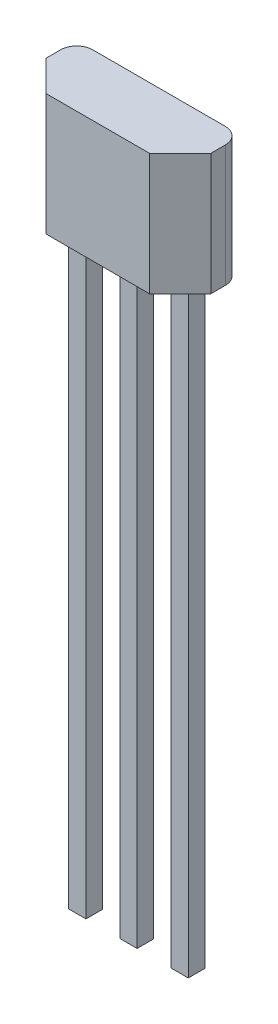
SolidWorks part; units mm, degrees
ref_plane "Front Plane" through (0, 0, 0) normal (0, 0, 1) x (1, 0, 0)
ref_plane "Top Plane" through (0, 0, 0) normal (0, 1, 0) x (1, 0, 0)
ref_plane "Right Plane" through (0, 0, 0) normal (1, 0, 0) x (0, 0, -1)
sketch "Sketch2" plane through (0, 0, 0) normal (0, 1, 0) x (1, 0, 0)
  line L0 (-2.045, 0) -> (2.045, 0) construction
  line L1 (-1.645, 0.76) -> (1.645, 0.76)
  line L2 (-2.045, 0.36) -> (-2.045, 0)
  line L3 (-1.285, -0.76) -> (1.285, -0.76)
  line L4 (2.045, 0.36) -> (2.045, 0)
  line L7 (-2.045, 0) -> (-1.285, -0.76)
  line L8 (2.045, 0) -> (1.285, -0.76)
  arc A0 (2.045, 0.36) -> (1.645, 0.76) centre (1.645, 0.36) ccw
  arc A1 (-1.645, 0.76) -> (-2.045, 0.36) centre (-1.645, 0.36) ccw
  point P1 (0, 0)
  point P9 (0, 0)
  dimension "D3" = 0.4
  dimension "D1" = 45
  dimension "D2" = 45
  dimension "D4" = 4.09
  dimension "D5" = 1.52
  dimension "D6" = 0.76
extrude "Boss-Extrude1" add sketch "Sketch2" along normal blind 3.02
ref_plane "Plane1" through (0, 0, 0) normal (0, 0, 1) x (1, 0, 0)
sketch "Sketch3" plane through (0, 0, 0) normal (0, 0, 1) x (1, 0, 0)
  line L0 (0, 0) -> (0, -2.9913) construction
  line L1 (0, -2.9913) -> (0, 3.02) construction
  line L2 (-1.285, 3.02) -> (1.285, 3.02) construction
  line L3 (-1.285, 0) -> (1.285, 0) construction
  line L4 (-0.215, 0) -> (0.215, 0)
  line L5 (-0.215, 0) -> (-0.215, -14.99)
  line L6 (-0.215, -14.99) -> (0.215, -14.99)
  line L7 (0.215, 0) -> (0.215, -14.99)
  line L8 (-0.215, 0) -> (0.215, -14.99) construction
  line L9 (-0.215, -14.99) -> (0.215, 0) construction
  line L10 (1.27, -14.99) -> (1.27, 0) construction
  line L11 (1.485, -14.99) -> (1.055, -14.99)
  line L12 (1.485, -14.99) -> (1.485, 0)
  line L13 (1.485, 0) -> (1.055, 0)
  line L14 (1.055, -14.99) -> (1.055, 0)
  line L15 (1.485, -14.99) -> (1.055, 0) construction
  line L16 (1.485, 0) -> (1.055, -14.99) construction
  line L17 (-1.485, 0) -> (-1.055, 0)
  line L18 (-1.485, 0) -> (-1.485, -14.99)
  line L19 (-1.485, -14.99) -> (-1.055, -14.99)
  line L20 (-1.055, 0) -> (-1.055, -14.99)
  line L21 (-1.485, 0) -> (-1.055, -14.99) construction
  line L22 (-1.485, -14.99) -> (-1.055, 0) construction
  line L23 (-1.27, -14.99) -> (-1.27, 0) construction
  point P10 (0, -7.495)
  point P17 (1.27, -7.495)
  point P22 (-1.27, -7.495)
  point P23 (0, 0)
  dimension "D1" = 0.43
  dimension "D2" = 0.43
  dimension "D3" = 0.43
  dimension "D6" = 14.99
  dimension "D7" = 14.99
  dimension "D8" = 14.99
  dimension "D5" = 1.27
  dimension "D4" = 1.27
extrude "Boss-Extrude2" add sketch "Sketch3" against normal blind 0.41
equation "\"D2@Sketch2\"=\"D1@Sketch2\""
equation "\"D6@Sketch2\"=\"D5@Sketch2\"/2"
equation "\"D2@Sketch3\"=\"D1@Sketch3\""
equation "\"D3@Sketch3\"=\"D1@Sketch3\""
equation "\"D6@Sketch3\"=\"D7@Sketch3\""
equation "\"D8@Sketch3\"=\"D6@Sketch3\""
equation "\"D4@Sketch3\"=\"D5@Sketch3\""
